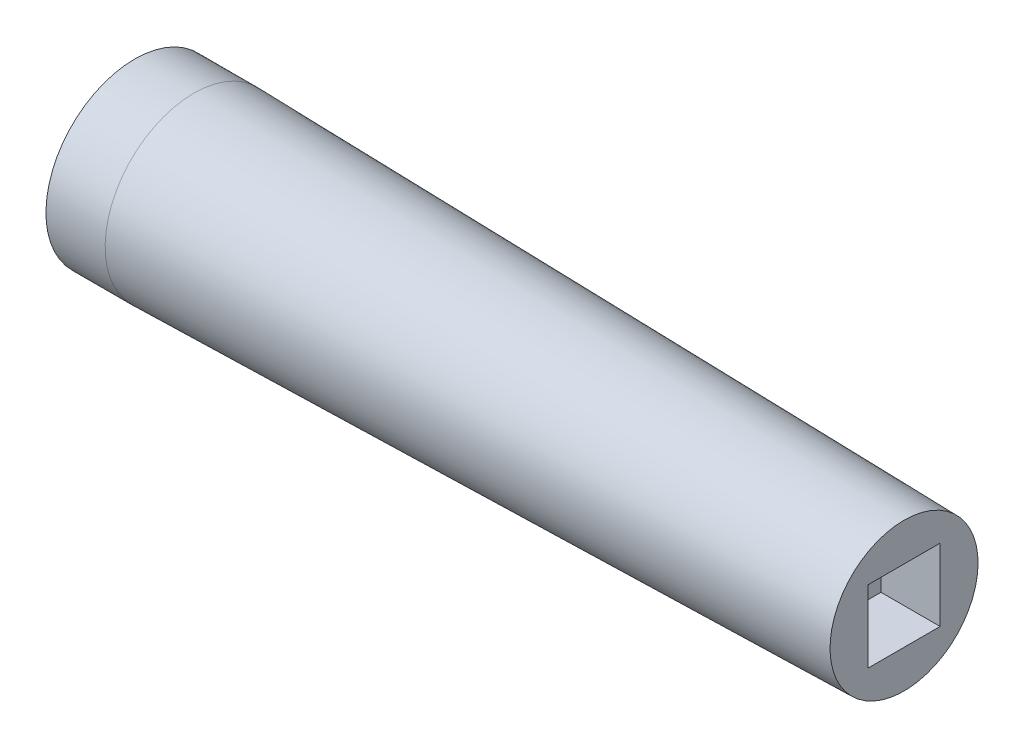
SolidWorks part; units mm, degrees
ref_plane "Front Plane" through (0, 0, 0) normal (0, 0, 1) x (1, 0, 0)
ref_plane "Top Plane" through (0, 0, 0) normal (0, 1, 0) x (1, 0, 0)
ref_plane "Right Plane" through (0, 0, 0) normal (1, 0, 0) x (0, 0, -1)
sketch "Sketch1" plane through (0, 0, 0) normal (0, 0, 1) x (1, 0, 0)
  line L0 (82.55, 0) -> (-82.55, 0)
  line L1 (-82.55, 0) -> (-82.55, 19.05)
  line L2 (-82.55, 19.05) -> (-69.85, 19.05)
  line L3 (82.55, 0) -> (82.55, 15.88)
  line L4 (82.55, 15.88) -> (-69.85, 19.05)
  point P4 (0, 0)
  dimension "D1" = 165.1
  dimension "D2" = 15.88
  dimension "D3" = 19.05
  dimension "D4" = 12.7
revolve "Revolve1" add sketch "Sketch1" angle 360 about L0
sketch "Sketch2" plane through (82.55, 0, 0) normal (1, 0, 0) x (0, 0, -1)
  line L1 (-7.745, -7.745) -> (7.745, -7.745)
  line L2 (-7.745, -7.745) -> (-7.745, 7.745)
  line L3 (-7.745, 7.745) -> (7.745, 7.745)
  line L4 (7.745, -7.745) -> (7.745, 7.745)
  line L5 (-7.745, -7.745) -> (7.745, 7.745) construction
  line L6 (-7.745, 7.745) -> (7.745, -7.745) construction
  point P0 (0, 0)
  dimension "D1" = 15.49
extrude "Cut-Extrude1" cut sketch "Sketch2" against normal blind 12.7
